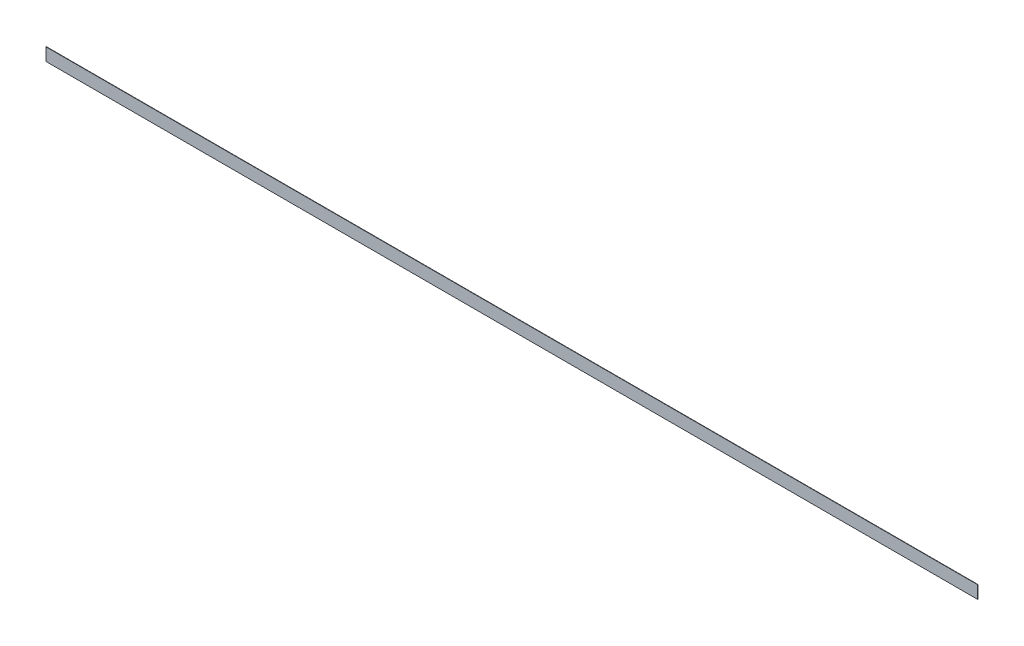
SolidWorks part; units mm, degrees
ref_plane "Front Plane" through (0, 0, 0) normal (0, 0, 1) x (1, 0, 0)
ref_plane "Top Plane" through (0, 0, 0) normal (0, 1, 0) x (1, 0, 0)
ref_plane "Right Plane" through (0, 0, 0) normal (1, 0, 0) x (0, 0, -1)
sketch "Sketch1" plane through (0, 0, 0) normal (0, 0, 1) x (1, 0, 0)
  line L1 (-375, -5.125) -> (375, -5.125)
  line L2 (-375, -5.125) -> (-375, 5.125)
  line L3 (-375, 5.125) -> (375, 5.125)
  line L4 (375, -5.125) -> (375, 5.125)
  line L5 (-375, -5.125) -> (375, 5.125) construction
  line L6 (-375, 5.125) -> (375, -5.125) construction
  point P0 (0, 0)
  dimension "D1" = 750
  dimension "D2" = 10.25
extrude "Boss-Extrude1" add sketch "Sketch1" along normal blind 0.3
